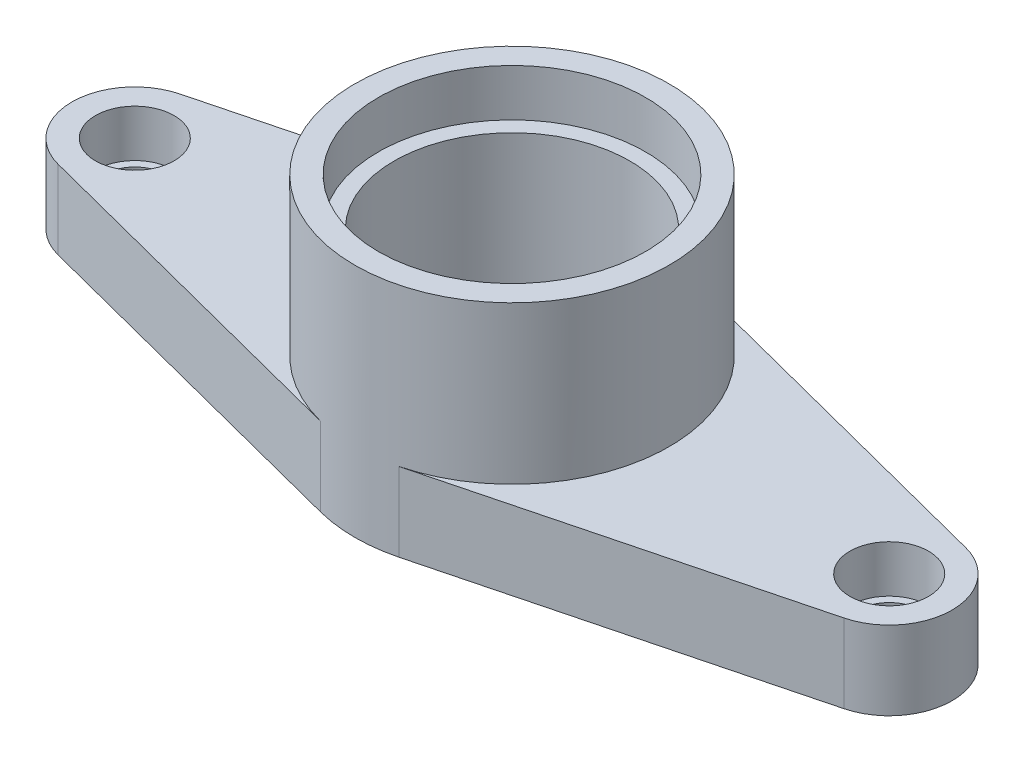
SolidWorks part; units mm, degrees
ref_plane "Alzado" through (0, 0, 0) normal (0, 0, 1) x (1, 0, 0)
ref_plane "Planta" through (0, 0, 0) normal (0, 1, 0) x (1, 0, 0)
ref_plane "Vista lateral" through (0, 0, 0) normal (1, 0, 0) x (0, 0, -1)
sketch "Croquis1" plane through (0, 0, 0) normal (0, 1, 0) x (1, 0, 0)
  line L0 (-357.3014, 0) -> (275.852, 0) construction
  line L1 (0, 161.7461) -> (0, -164.8197) construction
  line L2 (-125, 19.3649) -> (-12.5, 48.4123)
  line L3 (-125, -19.3649) -> (-12.5, -48.4123)
  line L4 (125, -19.3649) -> (12.5, -48.4123)
  line L5 (125, 19.3649) -> (12.5, 48.4123)
  arc A0 (-12.5, -48.4123) -> (12.5, -48.4123) centre (0, 0) ccw
  arc A1 (-125, 19.3649) -> (-125, -19.3649) centre (-120, 0) ccw
  arc A2 (125, -19.3649) -> (125, 19.3649) centre (120, 0) ccw
  arc A3 (12.5, 48.4123) -> (-12.5, 48.4123) centre (0, 0) ccw
  dimension "D1" = 100
  dimension "D2" = 40
  dimension "D3" = 120
extrude "Saliente-Extruir1" add sketch "Croquis1" along normal blind 25 contours L4 A0 L3 A1 L2 A3 L5 A2
sketch "Croquis2" plane through (0, 25, 0) normal (0, 1, 0) x (1, 0, 0)
  circle A0 centre (0, 0) radius 50
  arc A2 (12.5, 48.4123) -> (-12.5, 48.4123) centre (0, 0) ccw construction
extrude "Saliente-Extruir2" add sketch "Croquis2" along normal blind 50 contours A0
sketch "Croquis3" plane through (0, 75, 0) normal (0, 1, 0) x (1, 0, 0)
  circle A0 centre (0, 0) radius 42.5
  dimension "D1" = 85
extrude "Cortar-Extruir1" cut sketch "Croquis3" against normal blind 15 contours A0
sketch "Croquis4" plane through (0, 60, 0) normal (0, 1, 0) x (1, 0, 0)
  circle A0 centre (0, 0) radius 37.5
  dimension "D1" = 75
extrude "Cortar-Extruir2" cut sketch "Croquis4" against normal through all contours A0
sketch "Croquis5" plane through (0, 25, 0) normal (0, 1, 0) x (1, 0, 0)
  circle A0 centre (-120, 0) radius 12.5
  circle A1 centre (120, 0) radius 12.5
  arc A2 (-125, 19.3649) -> (-125, -19.3649) centre (-120, 0) ccw construction
  arc A3 (125, -19.3649) -> (125, 19.3649) centre (120, 0) ccw construction
extrude "Cortar-Extruir4" cut sketch "Croquis5" against normal blind 15 contours A1 | A0
sketch "Croquis6" plane through (0, 10, 0) normal (0, 1, 0) x (1, 0, 0)
  circle A0 centre (-120, 0) radius 10
  circle A1 centre (120, 0) radius 10
extrude "Cortar-Extruir6" cut sketch "Croquis6" against normal through all
